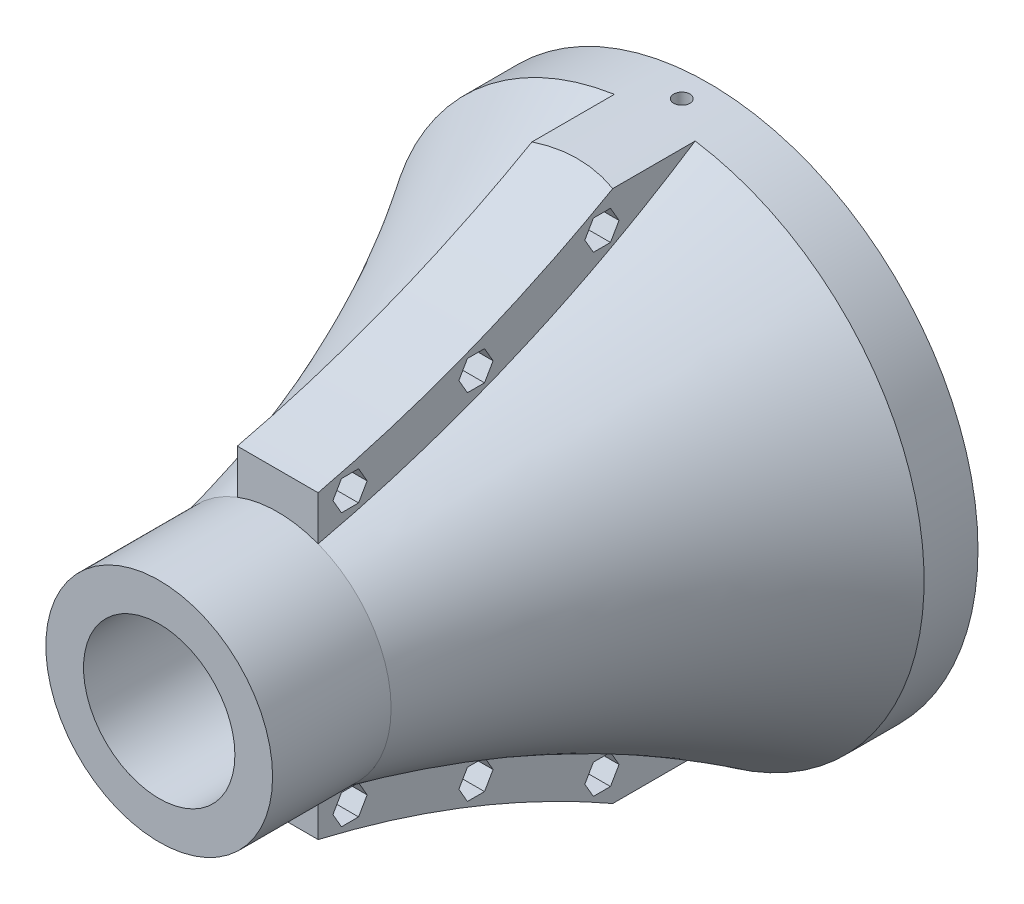
SolidWorks part; units mm, degrees
ref_plane "Front Plane" through (0, 0, 0) normal (0, 0, 1) x (1, 0, 0)
ref_plane "Top Plane" through (0, 0, 0) normal (0, 1, 0) x (1, 0, 0)
ref_plane "Right Plane" through (0, 0, 0) normal (1, 0, 0) x (0, 0, -1)
sketch "Sketch2" plane through (0, 0, 0) normal (0, 0, 1) x (1, 0, 0)
  circle A0 centre (0, 0) radius 30
  circle A1 centre (0, 0) radius 50
  dimension "D1" = 60
  dimension "D2" = 100
extrude "Boss-Extrude1" add sketch "Sketch2" along normal blind 10
sketch "Sketch3" plane through (0, 0, 0) normal (0, 1, 0) x (1, 0, 0)
  line L0 (50, 0) -> (-50, 0) construction
  line L1 (-50, -10) -> (50, -10) construction
  line L2 (50, 0) -> (-50, 0) construction
  line L3 (-50, -10) -> (50, -10) construction
  line L4 (-50, 0) -> (50, -10) construction
  circle A0 centre (0, -5) radius 1.5
  dimension "D1" = 3
extrude "Cut-Extrude1" cut sketch "Sketch3" against normal through all both and the other way through all
ref_plane "Motor-Start" through (0, 0, 30) normal (0, 0, 1) x (1, 0, 0)
sketch "Sketch5" plane through (0, 0, 30) normal (0, 0, 1) x (1, 0, 0)
  line L0 (-14.05, 14.05) -> (14.05, -14.05) construction
  line L1 (-14.05, 14.05) -> (14.05, 14.05)
  line L2 (-14.05, 14.05) -> (-14.05, -14.05)
  line L3 (-14.05, -14.05) -> (14.05, -14.05)
  line L4 (14.05, 14.05) -> (14.05, -14.05)
  line L5 (-21.05, 21.05) -> (-21.05, -21.05)
  line L6 (-21.05, -21.05) -> (21.05, -21.05)
  line L7 (21.05, 21.05) -> (21.05, -21.05)
  line L8 (-21.05, 21.05) -> (21.05, 21.05)
  dimension "D1" = 28.1
  dimension "D2" = 7
extrude "Boss-Extrude3" add sketch "Sketch5" along normal blind 32 separate body
sketch "Sketch6" plane through (0, 21.05, 0) normal (0, 1, 0) x (1, 0, 0)
  line L5 (21.05, -30) -> (-21.05, -30) construction
  line L6 (21.05, -30) -> (-21.05, -30) construction
  line L7 (-7.5, -32.5) -> (7.5, -32.5)
  line L8 (-7.5, -32.5) -> (-7.5, -42.5)
  line L9 (-7.5, -42.5) -> (7.5, -42.5)
  line L10 (7.5, -32.5) -> (7.5, -42.5)
  point P4 (0, -32.5)
  point P5 (0, -30)
  dimension "D1" = 10
  dimension "D2" = 15
  dimension "D3" = 2.5
extrude "Cut-Extrude2" cut sketch "Sketch6" against normal up to next (7 mm away)
sketch "Sketch7" plane through (0, 0, 62) normal (0, 0, 1) x (1, 0, 0)
  line L0 (14.05, -14.05) -> (14.05, 14.05) construction
  line L6 (21.05, 21.05) -> (-21.05, 21.05)
  line L7 (-21.05, 21.05) -> (-21.05, -21.05)
  line L8 (-21.05, -21.05) -> (21.05, -21.05)
  line L9 (21.05, -21.05) -> (21.05, 21.05)
  line L10 (21.05, 21.05) -> (-21.05, 21.05)
  line L11 (-21.05, 21.05) -> (-21.05, -21.05)
  line L12 (-21.05, -21.05) -> (21.05, -21.05)
  line L13 (21.05, -21.05) -> (21.05, 21.05)
  circle A0 centre (0, 0) radius 14.05
  dimension "D1" = 0
extrude "Boss-Extrude4" add sketch "Sketch7" along normal blind 40
sketch "Sketch11" plane through (0, 0, 102) normal (0, 0, 1) x (1, 0, 0)
  line L4 (21.05, -21.05) -> (21.05, 21.05)
  line L5 (21.05, 21.05) -> (-21.05, 21.05)
  line L6 (-21.05, 21.05) -> (-21.05, -21.05)
  line L7 (-21.05, -21.05) -> (21.05, -21.05)
  line L9 (0, 21.05) -> (-21.05, 21.05)
  line L10 (-21.05, 21.05) -> (-21.05, 0)
  arc A0 (0, 21.05) -> (-21.05, 0) centre (0, 0) ccw
  dimension "D1" = 0
extrude "Cut-Extrude3" cut sketch "Sketch11" against normal up to surface (72 mm away)
pattern_circular "CirPattern1" count 4 over 360 about axis through (0, 0, 102) along (0, 0, 1) of "Cut-Extrude3"
sketch "Sketch10" plane through (0, 0, 0) normal (0, 1, 0) x (1, 0, 0)
  line L0 (-50, -10) -> (50, -10) construction
  line L1 (-50, -10) -> (-30, -10)
  line L6 (0, 0) -> (0, -21.7399) construction
  line L8 (-21.05, -30) -> (-21.05, -80)
  line L9 (-21.05, -30) -> (-21.05, -102) construction
  spline S0 degree 2 poles (-30, -10) (-20.5781, -18.0733) (-21.05, -30) knots 0 0 0 1 1 1
  spline S1 degree 2 poles (-50, -10) (-29.0913, -42.247) (-21.05, -80) knots 0 0 0 1 1 1
  dimension "D1" = 50
revolve "Revolve2" add sketch "Sketch10" angle 360 about L6
sketch "Sketch12" plane through (0, 0, 30) normal (0, 0, -1) x (-1, 0, 0)
  line L0 (-14.05, 14.05) -> (14.05, 14.05) construction
  line L1 (14.05, 14.05) -> (14.05, -14.05) construction
  line L2 (14.05, -14.05) -> (-14.05, -14.05) construction
  line L3 (-14.05, -14.05) -> (-14.05, 14.05) construction
  line L4 (-10.05, -10.05) -> (-10.05, 10.05)
  line L5 (-10.05, 10.05) -> (10.05, 10.05)
  line L6 (10.05, 10.05) -> (10.05, -10.05)
  line L7 (10.05, -10.05) -> (-10.05, -10.05)
  circle A1 centre (0, 0) radius 21.05
  circle A2 centre (0, 0) radius 21.05
  dimension "D2" = 4
  dimension "D1" = 0
extrude "Boss-Extrude5" add sketch "Sketch12" along normal blind 10
ref_plane "Plane1" through (0, -50, 0) normal (0, -1, 0) x (-1, 0, 0)
sketch "Sketch14" plane through (0, -50, 0) normal (0, -1, 0) x (-1, 0, 0)
  line L0 (0, 0) -> (0, -102) construction
  line L1 (-21.05, -102) -> (21.05, -102) construction
  line L2 (21.05, -80) -> (-21.05, -80) construction
  line L3 (-7.5, -10) -> (7.5, -10)
  line L4 (-7.5, -10) -> (-7.5, -80)
  line L5 (-7.5, -80) -> (7.5, -80)
  line L6 (7.5, -10) -> (7.5, -80)
  line L7 (-7.5, -10) -> (7.5, -80) construction
  line L8 (-50, -10) -> (50, -10) construction
  point P11 (0, -45)
  dimension "D1" = 15
extrude "Boss-Extrude7" add sketch "Sketch14" against normal up to surface (0.5657 mm away)
mirror "Mirror1" about plane through (0, 0, 0) normal (0, 1, 0) of "Boss-Extrude7"
sketch "Sketch18" plane through (7.5, 0, 0) normal (1, 0, 0) x (0, 0, -1)
  line L0 (-15.5392, -55.7721) -> (-15.5392, -55.7721)
  line L3 (-80, -19.6686) -> (-80, -50)
  line L4 (-80, -50) -> (-10, -50)
  line L5 (-10, -50) -> (-10, -49.4343)
  line L8 (-10, -50) -> (-10, -49.4343) construction
  line L14 (0, 0) -> (-102, 0) construction
  line L15 (-102, 21.05) -> (-102, -21.05) construction
  line L16 (-16.3703, 54.8393) -> (-16.3703, 54.8393)
  line L17 (-80, 19.6686) -> (-80, 27.8819) construction
  line L18 (-80, 19.6686) -> (-80, 50) construction
  line L19 (-80, 50) -> (-80, 19.6686)
  line L20 (-10, 49.4343) -> (-10, 50)
  line L21 (-10, 50) -> (-80, 50)
  line L23 (-10, 49.4343) -> (-10, 50) construction
  line L25 (-10, 50) -> (-24.3173, 50) construction
  line L26 (-10, 50) -> (-80, 50) construction
  line L27 (-80, 27.8819) -> (-95.5499, 45.3001)
  line L28 (-95.5499, 45.3001) -> (-64.8581, 70.7188)
  line L29 (-64.8581, 70.7188) -> (-24.3173, 50)
  line L30 (-10, -49.4343) -> (-80, -19.6686) construction
  line L31 (-15.5392, -55.7721) -> (-83.1305, -27.0306) construction
  spline S1 degree 3 poles (171.8762, -1032.7551) (196.554, -536.7728) (164.8517, -136.6464) (-32.0569, -36.7324) (-37.8028, -33.9779) (-40.7125, -32.6629) (-46.5803, -30.1688) (-49.5404, -28.9886) (-55.5128, -26.7613) (-58.5273, -25.7134) (-266.3643, 41.3893) (-558.3436, -202.9928) (-893.5136, -601.21) knots -8.296922 -8.296922 -8.296922 -8.296922 0.25 0.375 0.375 0.5 0.5 0.625 0.625 0.75 0.75 9.185358 9.185358 9.185358 9.185358 only from (-10, -49.4343) to (-80, -19.6686)
  spline S4 degree 1 poles (-81.7781, 27.4685) (-16.3703, 54.8393) knots 0 0 1 1 construction
  spline S5 degree 3 poles (-2066.8594, 2220.2794) (-1285.0239, 1084.5152) (-486.0435, -112.3154) (-58.5273, 25.7134) (-55.5128, 26.7613) (-49.5404, 28.9886) (-46.5803, 30.1688) (-40.7125, 32.6629) (-37.8028, 33.9779) (-32.0569, 36.7324) (411.605, 261.8523) (16.577, 2011.0368) (21.4345, 3026.9526) knots -17.233468 -17.233468 -17.233468 -17.233468 0.25 0.25 0.375 0.375 0.5 0.5 0.625 0.625 0.75 20.16402 20.16402 20.16402 20.16402 only from (-80, 19.6686) to (-10, 49.4343)
  spline S6 degree 3 poles (-80, 19.6686) (-73.7782, 21.0869) (-67.6319, 22.7738) (-58.5273, 25.7134) (-55.5128, 26.7613) (-49.5404, 28.9886) (-46.5803, 30.1688) (-40.7125, 32.6629) (-37.8028, 33.9779) (-32.0569, 36.7324) (-23.542, 41.0529) (-15.336, 45.9349) (-10, 49.4343) knots 0 0 0 0 0.25 0.25 0.375 0.375 0.5 0.5 0.625 0.625 0.75 1 1 1 1 construction
  spline S7 degree 3 poles (-81.7781, 27.4685) (-81.3337, 27.5698) (-80.5918, 27.7414) (-74.8046, 29.1135) (-63.7882, 32.1854) (-47.7607, 38.0816) (-35.1429, 44.0189) (-26.7656, 48.5782) (-21.6344, 51.5475) (-18.3279, 53.5867) (-16.3703, 54.8393) knots 0 0 0 0 0.018561 0.030935 0.241989 0.483978 0.725968 0.809917 0.873133 0.967957 0.967957 0.967957 0.967957 only from (-80, 27.8819) to (-24.3173, 50)
  dimension "D3" = 0
  dimension "D1" = 0
  dimension "D2" = 8
  dimension "D4" = 8
extrude "Cut-Extrude4" cut sketch "Sketch18" against normal through all contours L27 S7 L29 L28
mirror "Mirror2" about plane through (0, 0, 0) normal (0, 1, 0) of "Cut-Extrude4"
sketch "Sketch16" plane through (7.5, 0, 0) normal (1, 0, 0) x (0, 0, -1)
  line L0 (-75.665, -27.9889) -> (-72.4895, -27.9889)
  line L3 (-72.4895, -22.4889) -> (-75.665, -22.4889)
  line L6 (-72.4895, -27.9889) -> (-70.9018, -25.2389)
  line L7 (-70.9018, -25.2389) -> (-72.4895, -22.4889)
  line L8 (-75.665, -22.4889) -> (-77.2527, -25.2389)
  line L9 (-77.2527, -25.2389) -> (-75.665, -27.9889)
  line L10 (-75.665, -22.4889) -> (-72.4895, -27.9889) construction
  line L11 (-28.9016, -46.4847) -> (-25.7262, -46.4847)
  line L12 (-25.7262, -40.9847) -> (-28.9016, -40.9847)
  line L13 (-25.7262, -46.4847) -> (-24.1384, -43.7347)
  line L14 (-24.1384, -43.7347) -> (-25.7262, -40.9847)
  line L15 (-28.9016, -40.9847) -> (-30.4893, -43.7347)
  line L16 (-30.4893, -43.7347) -> (-28.9016, -46.4847)
  line L17 (-28.9016, -40.9847) -> (-25.7262, -46.4847) construction
  line L18 (-52.2833, -35.6075) -> (-49.1078, -35.6075)
  line L19 (-49.1078, -30.1075) -> (-52.2833, -30.1075)
  line L20 (-49.1078, -35.6075) -> (-47.5201, -32.8575)
  line L21 (-47.5201, -32.8575) -> (-49.1078, -30.1075)
  line L22 (-52.2833, -30.1075) -> (-53.871, -32.8575)
  line L23 (-53.871, -32.8575) -> (-52.2833, -35.6075)
  line L24 (-52.2833, -30.1075) -> (-49.1078, -35.6075) construction
  line L25 (-79.0772, -23.9898) -> (-79.0772, -19.881) construction
  line L26 (-22.3139, -46.5379) -> (-22.3139, -41.9308) construction
  line L27 (-50.6956, -33.7572) -> (-50.6956, -39.8786) construction
  line L28 (0, 0) -> (-108.4337, 0) construction
  line L29 (-30.4893, 43.7347) -> (-28.9016, 46.4847)
  line L30 (-28.9016, 40.9847) -> (-30.4893, 43.7347)
  line L31 (-25.7262, 40.9847) -> (-28.9016, 40.9847)
  line L32 (-24.1384, 43.7347) -> (-25.7262, 40.9847)
  line L33 (-25.7262, 46.4847) -> (-24.1384, 43.7347)
  line L34 (-28.9016, 46.4847) -> (-25.7262, 46.4847)
  line L35 (-53.871, 32.8575) -> (-52.2833, 35.6075)
  line L36 (-52.2833, 30.1075) -> (-53.871, 32.8575)
  line L37 (-49.1078, 30.1075) -> (-52.2833, 30.1075)
  line L38 (-47.5201, 32.8575) -> (-49.1078, 30.1075)
  line L39 (-49.1078, 35.6075) -> (-47.5201, 32.8575)
  line L40 (-52.2833, 35.6075) -> (-49.1078, 35.6075)
  line L41 (-75.665, 22.4889) -> (-77.2527, 25.2389)
  line L42 (-72.4895, 22.4889) -> (-75.665, 22.4889)
  line L43 (-70.9018, 25.2389) -> (-72.4895, 22.4889)
  line L44 (-72.4895, 27.9889) -> (-70.9018, 25.2389)
  line L45 (-75.665, 27.9889) -> (-72.4895, 27.9889)
  line L46 (-77.2527, 25.2389) -> (-75.665, 27.9889)
  spline S0 degree 3 poles (-3028.1658, 525.9222) (-241.3882, -33.363) (-149.225, -8.361) (-63.7882, -32.1854) (-47.7607, -38.0816) (-35.1429, -44.0189) (119.8392, -128.3674) (163.4755, -392.1982) (2202.949, -2056.7223) knots -3.125531 -3.125531 -3.125531 -3.125531 0.030935 0.241989 0.483978 0.725968 0.809917 7.683427 7.683427 7.683427 7.683427 only from (-80, -27.8819) to (-24.3173, -50) construction
  spline S1 degree 3 poles (-80, -27.8819) (-79.852, -27.917) (-74.6581, -29.1543) (-63.7882, -32.1854) (-47.7607, -38.0816) (-35.1429, -44.0189) (-27.446, -48.2079) (-24.9877, -49.612) (-24.3173, -50) knots 0.024748 0.024748 0.024748 0.024748 0.030935 0.241989 0.483978 0.725968 0.809917 0.841525 0.841525 0.841525 0.841525 construction
  spline S2 degree 1 poles (-79.0772, -23.9898) (-22.3139, -46.5379) knots 0 0 1 1 construction
  spline S3 degree 3 poles (-79.0772, -23.9898) (-77.8242, -24.2869) (-75.738, -24.8014) (-70.794, -26.1) (-63.732, -28.16) (-55.1684, -31.0922) (-45.652, -34.8211) (-37.0693, -38.6717) (-30.117, -42.2111) (-25.6333, -44.6452) (-23.5545, -45.82) (-22.3139, -46.5379) knots 0.024748 0.024748 0.024748 0.024748 0.076204 0.110507 0.228942 0.370027 0.472125 0.637331 0.745903 0.784152 0.841525 0.841525 0.841525 0.841525 construction
  spline S4 degree 3 poles (-80, -19.6686) (-73.7782, -21.0869) (-67.6319, -22.7738) (-58.5273, -25.7134) (-55.5128, -26.7613) (-49.5404, -28.9886) (-46.5803, -30.1688) (-40.7125, -32.6629) (-37.8028, -33.9779) (-32.0569, -36.7324) (-23.542, -41.0529) (-15.336, -45.9349) (-10, -49.4343) knots 0 0 0 0 0.25 0.25 0.375 0.375 0.5 0.5 0.625 0.625 0.75 1 1 1 1 construction
  point P10 (-74.0772, -25.2389)
  point P30 (-27.3139, -43.7347)
  point P41 (-50.6956, -32.8575)
  dimension "D1" = 5.5
  dimension "D2" = 120
  dimension "D3" = 120
  dimension "D4" = 120
  dimension "D5" = 120
  dimension "D7" = 5
  dimension "D8" = 5.5
  dimension "D9" = 120
  dimension "D10" = 120
  dimension "D11" = 120
  dimension "D12" = 120
  dimension "D13" = 5
  dimension "D14" = 120
  dimension "D15" = 120
  dimension "D16" = 120
  dimension "D17" = 120
  dimension "D18" = 5.5
  dimension "D19" = 28.3817
  dimension "D6" = 4
extrude "Cut-Extrude5" cut sketch "Sketch16" against normal blind 5
sketch "Sketch19" plane through (7.5, 0, 0) normal (1, 0, 0) x (0, 0, -1)
  line L0 (-75.665, -22.4889) -> (-72.4895, -27.9889) construction
  line L1 (-52.2833, -30.1075) -> (-49.1078, -35.6075) construction
  line L2 (-28.9016, -40.9847) -> (-25.7262, -46.4847) construction
  line L5 (0, 0) -> (-102, 0) construction
  line L6 (-102, 21.05) -> (-102, -21.05) construction
  circle A0 centre (-27.3139, -43.7347) radius 1.65
  circle A1 centre (-50.6956, -32.8575) radius 1.65
  circle A2 centre (-74.0772, -25.2389) radius 1.65
  circle A3 centre (-27.3139, 43.7347) radius 1.65
  circle A4 centre (-50.6956, 32.8575) radius 1.65
  circle A5 centre (-74.0772, 25.2389) radius 1.65
  dimension "D1" = 3.3
extrude "Cut-Extrude6" cut sketch "Sketch19" against normal through all
sketch "Sketch20" plane through (-7.5, 0, 0) normal (-1, 0, 0) x (0, 0, 1)
  line L0 (0, 0) -> (102, 0) construction
  line L1 (102, -21.05) -> (102, 21.05) construction
  circle A0 centre (74.0772, 25.2389) radius 2.875
  circle A1 centre (50.6956, 32.8575) radius 2.875
  circle A2 centre (27.3139, 43.7347) radius 2.875
  circle A3 centre (74.0772, -25.2389) radius 2.875
  circle A4 centre (50.6956, -32.8575) radius 2.875
  circle A5 centre (27.3139, -43.7347) radius 2.875
  dimension "D1" = 5.75
extrude "Cut-Extrude7" cut sketch "Sketch20" against normal blind 5
sketch "Sketch21" plane through (0, 0, 0) normal (0, 0, -1) x (-1, 0, 0)
  circle A0 centre (0, 0) radius 62
  circle A1 centre (0, 0) radius 50
  circle A2 centre (0, 0) radius 50
  dimension "D2" = 12
  dimension "D1" = 0
extrude "Cut-Extrude8" cut sketch "Sketch21" against normal through all both and the other way through all
